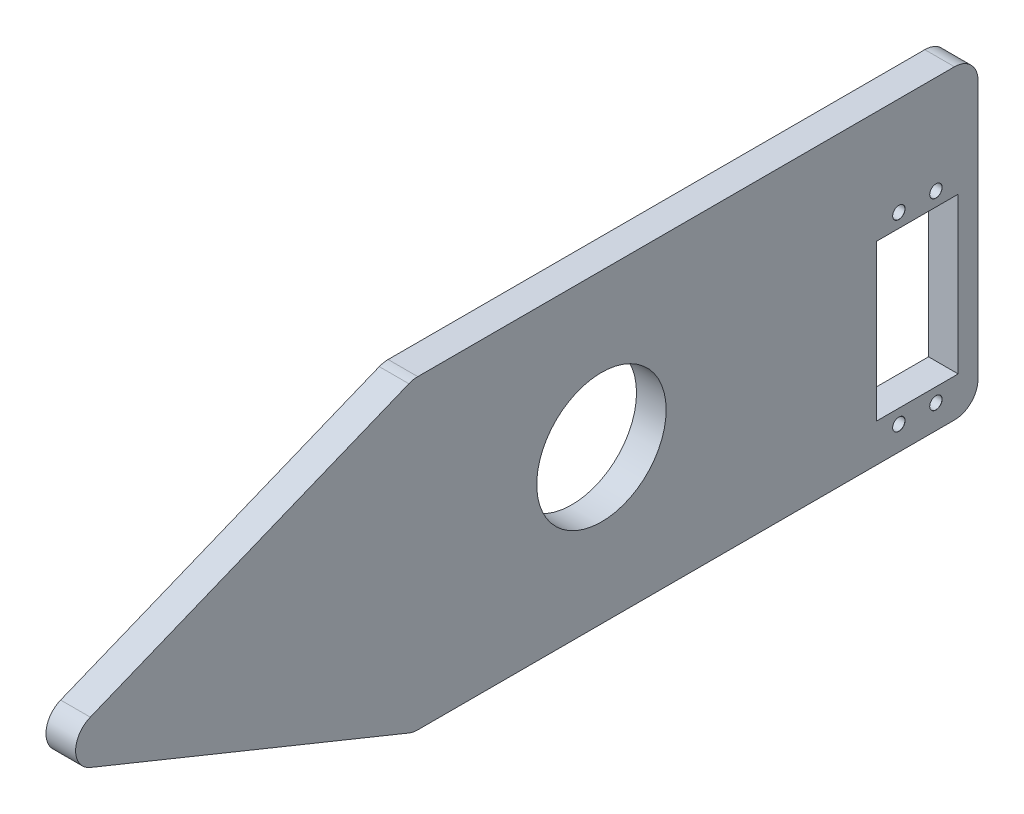
SolidWorks part; units mm, degrees
ref_plane "Front Plane" through (0, 0, 0) normal (1, 0, 0) x (0, 1, 0)
ref_plane "Top Plane" through (0, 0, 0) normal (0, 0, 1) x (0, 1, 0)
ref_plane "Right Plane" through (0, 0, 0) normal (0, 1, 0) x (-1, 0, 0)
sketch "Sketch1" plane through (0, 0, 0) normal (1, 0, 0) x (0, 1, 0)
  line L0 (-41.275, 50.8) -> (-41.275, -101.6)
  line L1 (-41.275, -101.6) -> (41.275, -101.6)
  line L2 (41.275, -101.6) -> (41.275, 50.8)
  line L3 (41.275, 50.8) -> (0, 152.4)
  line L4 (0, 152.4) -> (-41.275, 50.8)
  line L5 (0, 152.4) -> (0, 0) construction
  line L6 (-41.275, 50.8) -> (0, 50.8) construction
  line L7 (0, 50.8) -> (41.275, 50.8) construction
  line L8 (-448.1018, -246.5596) -> (346.2414, -246.5596) construction
  circle A0 centre (0, 0) radius 6.35 construction
  circle A1 centre (0, 0) radius 17.4625
  dimension "D5" = 12.7
  dimension "D6" = 34.925
  dimension "D1" = 152.4
  dimension "D2" = 254
  dimension "D3" = 101.6
  dimension "D4" = 82.55
  dimension "D7" = 246.5596
sketch "Sketch2" plane through (0, 0, 0) normal (1, 0, 0) x (0, 1, 0)
  line L0 (-37.25, -85.25) -> (-30, -85.25) construction
  line L1 (-30, -75.25) -> (10, -75.25)
  line L2 (-30, -75.25) -> (-30, -95.25)
  line L3 (-30, -95.25) -> (10, -95.25)
  line L9 (-30, -76.25) -> (-37.25, -76.25)
  line L10 (-30, -76.25) -> (-30, -94.25)
  line L11 (-30, -94.25) -> (-37.25, -94.25)
  line L12 (-37.25, -76.25) -> (-37.25, -94.25)
  line L13 (10, -75.25) -> (10, -95.25)
  line L14 (-10, -75.25) -> (-10, -95.25) construction
  line L15 (10, -94.25) -> (17.25, -94.25)
  line L16 (17.25, -76.25) -> (17.25, -94.25)
  line L17 (10, -76.25) -> (17.25, -76.25)
  line L18 (-34.75, -76.25) -> (-34.75, -80.25) construction
  line L19 (-34.75, -80.25) -> (-34.75, -90.25) construction
  line L20 (-34.75, -90.25) -> (-34.75, -94.25) construction
  line L21 (14.75, -90.25) -> (14.75, -94.25) construction
  line L22 (14.75, -80.25) -> (14.75, -90.25) construction
  line L23 (14.75, -76.25) -> (14.75, -80.25) construction
  line L24 (0, -85.25) -> (10, -85.25) construction
  line L25 (0, 0) -> (0, -85.25) construction
  line L26 (-41.275, -101.6) -> (41.275, -101.6) construction
  circle A0 centre (0, -85.25) radius 3.9853
  circle A1 centre (-34.75, -80.25) radius 2.1
  dimension "D9" = 4.2
  dimension "D1" = 40
  dimension "D2" = 54.5
  dimension "D3" = 10
  dimension "D4" = 49.5
  dimension "D5" = 20
  dimension "D6" = 1
  dimension "D7" = 10
  dimension "D8" = 6.35
extrude "Boss-Extrude2" add sketch "Sketch1" along normal mid plane 8.001
fillet "Fillet1" radius 6.35 5 edges at (0, 41.275, -101.6) (0, -41.275, -101.6) (0, 0, 152.4) (0, -41.275, 50.8) (0, 41.275, 50.8)
hole_wizard "Tap Drill for M4x0.7 Tap1" positions "Sketch3" profile "Sketch4" hole size "M4x0.7" standard "ANSI Metric" end condition through all
sketch "Sketch3" plane through (4.0005, 0, 0) normal (1, 0, 0) x (0, 1, 0)
  point P0 (-34.75, -80.25)
  point P3 (-34.75, -90.25)
  point P6 (14.75, -80.25)
  point P9 (14.75, -90.25)
sketch "Sketch4" plane through (4.0005, -34.75, -80.25) normal (0, 1, 0) x (0, 0, -1)
  line L0 (0, 0) -> (0, 8.001)
  line L1 (0, 8.001) -> (1.65, 8.001)
  line L2 (1.65, 8.001) -> (1.65, 0.025)
  line L3 (1.65, 0.025) -> (1.675, 0)
  line L5 (1.675, 0) -> (0, 0)
  line L6 (-1.65, 0.025) -> (-1.675, 0) construction
  line L11 (0, -6.35) -> (0, 107.95) construction
  dimension "Thru Hole Dia." = 3.3
  dimension "Thru Hole Depth" = 8.001
  dimension "Near C'Sink Dia." = 3.35
  dimension "Near C'Sink Angle" = 90
sketch "Sketch5" plane through (4.0005, 0, 0) normal (1, 0, 0) x (0, 1, 0)
  line L8 (11, -96.25) -> (11, -74.25)
  line L9 (-31, -96.25) -> (11, -96.25)
  line L10 (-31, -74.25) -> (-31, -96.25)
  line L11 (11, -74.25) -> (-31, -74.25)
  line L12 (11, -96.25) -> (11, -74.25)
  line L13 (-31, -96.25) -> (11, -96.25)
  line L14 (-31, -74.25) -> (-31, -96.25)
  line L15 (11, -74.25) -> (-31, -74.25)
  dimension "D1" = 1
extrude "Cut-Extrude1" cut sketch "Sketch5" against normal through all
